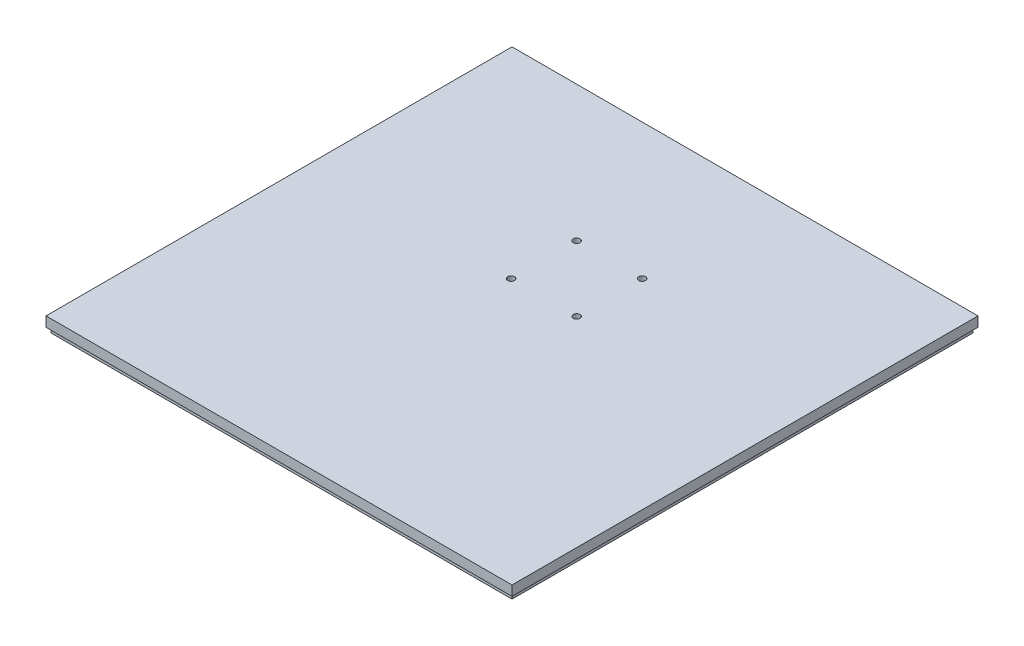
SolidWorks part; units mm, degrees
ref_plane "Front Plane" through (0, 0, 0) normal (0, 0, 1) x (1, 0, 0)
ref_plane "Top Plane" through (0, 0, 0) normal (0, 1, 0) x (1, 0, 0)
ref_plane "Right Plane" through (0, 0, 0) normal (1, 0, 0) x (0, 0, -1)
sketch "Sketch1" plane through (-151.1137, 667.5271, 96.7382) normal (0, 1, 0) x (1, 0, 0)
  line L1 (-145.7488, -200.1243) -> (447.9762, -200.1243)
  line L2 (-145.7488, -200.1243) -> (-145.7488, 393.6007)
  line L3 (-145.7488, 393.6007) -> (447.9762, 393.6007)
  line L4 (447.9762, -200.1243) -> (447.9762, 393.6007)
  line L5 (-145.7488, -200.1243) -> (447.9762, 393.6007) construction
  line L6 (-145.7488, 393.6007) -> (447.9762, -200.1243) construction
  point P0 (151.1137, 96.7382)
  dimension "D1" = 593.725
extrude "Boss-Extrude1" add sketch "Sketch1" along normal blind 19.05
sketch "Sketch3" plane through (0, 686.5771, 0) normal (0, 1, 0) x (1, 0, 0)
  line L8 (300.0375, -300.0375) -> (300.0375, 300.0375)
  line L9 (300.0375, 300.0375) -> (-300.0375, 300.0375)
  line L10 (-300.0375, 300.0375) -> (-300.0375, -300.0375)
  line L11 (-300.0375, -300.0375) -> (300.0375, -300.0375)
  line L12 (300.0375, -300.0375) -> (300.0375, 300.0375)
  line L13 (300.0375, 300.0375) -> (-300.0375, 300.0375)
  line L14 (-300.0375, 300.0375) -> (-300.0375, -300.0375)
  line L15 (-300.0375, -300.0375) -> (300.0375, -300.0375)
  dimension "D1" = 3.175
extrude "Boss-Extrude2" add sketch "Sketch3" against normal blind 12.7
sketch "Sketch4" plane through (0, 667.5271, 0) normal (0, -1, 0) x (1, 0, 0)
  line L2 (0, 296.8625) -> (0, -296.8625) construction
  line L3 (-296.8625, 296.8625) -> (296.8625, 296.8625) construction
  line L4 (296.8625, -296.8625) -> (-296.8625, -296.8625) construction
  circle A1 centre (42.2072, -40.9981) radius 4.3656
  circle A2 centre (-42.2072, -40.9981) radius 4.3656
  circle A3 centre (-42.2072, -125.4125) radius 4.3656
  circle A4 centre (42.2072, -125.4125) radius 4.3656
  point P8 (0, -79.9029)
  dimension "D1" = 42.2072
  dimension "D2" = 8.7312
  dimension "D4" = 84.4144
  dimension "D5" = 84.4144
  dimension "D3" = 171.45
extrude "Cut-Extrude1" cut sketch "Sketch4" against normal blind 19.05
